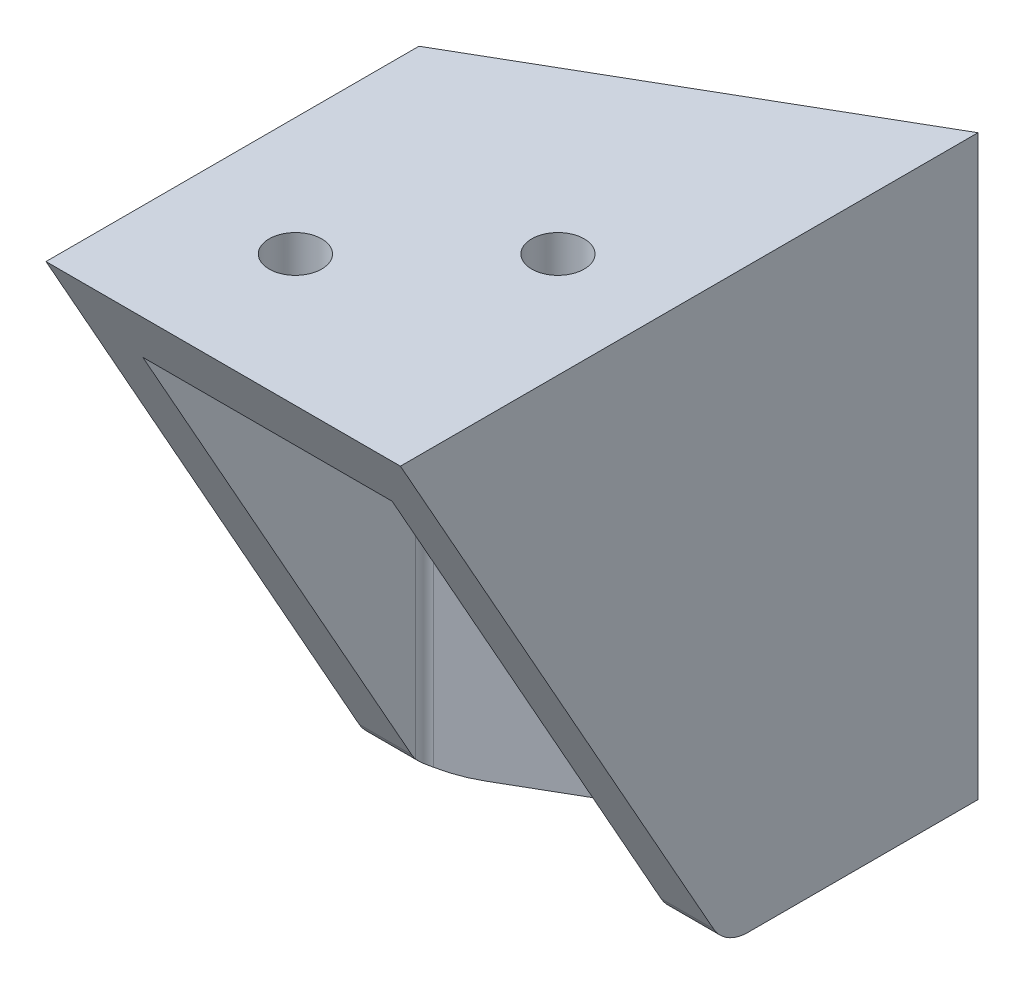
SolidWorks part; units mm, degrees
ref_plane "Front Plane" through (0, 0, 0) normal (0, 0, 1) x (1, 0, 0)
ref_plane "Top Plane" through (0, 0, 0) normal (0, 1, 0) x (1, 0, 0)
ref_plane "Right Plane" through (0, 0, 0) normal (1, 0, 0) x (0, 0, -1)
sketch "Sketch1" plane through (0, 0, 0) normal (0, 1, 0) x (1, 0, 0)
  line L1 (-13.5, -22) -> (13.5, -22)
  line L2 (-13.5, -22) -> (-13.5, 22)
  line L3 (-13.5, 22) -> (13.5, 22)
  line L4 (13.5, -22) -> (13.5, 22)
  line L5 (-13.5, -22) -> (13.5, 22) construction
  line L6 (-13.5, 22) -> (13.5, -22) construction
  point P0 (0, 0)
  dimension "D1" = 27
  dimension "D2" = 44
extrude "Boss-Extrude1" add sketch "Sketch1" along normal blind 6
sketch "Sketch2" plane through (0, 6, 0) normal (0, 1, 0) x (1, 0, 0)
  line L0 (13.5, 22) -> (-13.5, 6.4115)
  line L1 (-13.5, 22) -> (-13.5, -22) construction
  line L2 (-13.5, 6.4115) -> (-13.5, 22)
  line L3 (-13.5, 22) -> (13.5, 22)
  dimension "D1" = 30
extrude "Cut-Extrude1" cut sketch "Sketch2" against normal through all
sketch "Sketch3" plane through (0, 6, 0) normal (0, 1, 0) x (1, 0, 0)
  line L0 (-13.5, 6.4115) -> (13.5, 22)
  line L1 (13.5, 22) -> (13.5, 16)
  line L2 (13.5, -22) -> (13.5, 22) construction
  line L3 (13.5, 16) -> (-13.5, 0.4115)
  line L4 (-13.5, 6.4115) -> (-13.5, -22) construction
  line L5 (-13.5, 0.4115) -> (-13.5, 6.4115)
  dimension "D1" = 6
extrude "Boss-Extrude2" add sketch "Sketch3" against normal blind 44
sketch "Sketch4" plane through (0, 0, 0) normal (0, -1, 0) x (1, 0, 0)
  line L2 (-13.5, 22) -> (13.5, 22) construction
  line L3 (-13.5, -0.4115) -> (-13.5, 22) construction
  circle A0 centre (-4.5, 12) radius 2
  circle A1 centre (5.5, 2) radius 2
  dimension "D5" = 4
  dimension "D6" = 4
  dimension "D1" = 10
  dimension "D2" = 10
  dimension "D3" = 9
  dimension "D4" = 10
extrude "Cut-Extrude2" cut sketch "Sketch4" against normal through all
ref_plane "Plane1" through (-6.1513, 0, -10.6543) normal (-0.5, 0, -0.866) x (-0.866, 0, 0.5)
sketch "Sketch7" plane through (-6.1513, 0, -10.6543) normal (-0.5, 0, -0.866) x (-0.866, 0, 0.5)
  line L2 (-22.6913, -38) -> (8.4856, -38) construction
  line L3 (8.4856, -38) -> (8.4856, 6) construction
  circle A0 centre (-5.5144, -13) radius 2.05
  circle A1 centre (-0.5144, -25.5) radius 2.05
  dimension "D4" = 4.1
  dimension "D5" = 4.1
  dimension "D1" = 12.5
  dimension "D2" = 9
  dimension "D3" = 5
  dimension "D6" = 12.5
extrude "Cut-Extrude4" cut sketch "Sketch7" against normal through all
ref_plane "Plane2" through (-9.5, 0, 0) normal (-1, 0, 0) x (0, 0, 1)
sketch "Sketch12" plane through (-9.5, 0, 0) normal (-1, 0, 0) x (0, 0, 1)
  line L6 (-2.7209, -38) -> (-2.7209, 0)
  line L9 (-2.7209, 0) -> (22, 0)
  line L10 (22, 0) -> (22, -38)
  line L11 (22, -38) -> (-2.7209, -38)
ref_plane "Plane3" through (-13.5, 0, 0) normal (-1, 0, 0) x (0, 0, 1)
ref_plane "Plane4" through (13.5, 0, 0) normal (1, 0, 0) x (0, 0, -1)
ref_plane "Plane5" through (9.5, 0, 0) normal (1, 0, 0) x (0, 0, -1)
sketch "Sketch15" plane through (9.5, 0, 0) normal (1, 0, 0) x (0, 0, -1)
  line L0 (-22, 0) -> (13.6906, 0)
  line L3 (13.6906, 0) -> (13.6906, -38)
  line L7 (-22, 0) -> (-22, -38)
  line L8 (-22, -38) -> (13.6906, -38)
sketch "Sketch17" plane through (13.5, 0, 0) normal (1, 0, 0) x (0, 0, -1)
  line L0 (-22, 0) -> (16, 0)
  line L1 (16, 0) -> (16, -38)
  line L3 (-22, 0) -> (-22, -38)
  line L4 (-22, -38) -> (16, -38)
loft "Loft5" add profiles "Sketch15", "Sketch17"
sketch "Sketch20" plane through (-13.5, 0, 0) normal (-1, 0, 0) x (0, 0, 1)
  line L1 (-0.4115, 0) -> (22, 0)
  line L2 (-0.4115, 0) -> (-0.4115, -38)
  line L3 (-0.4115, -38) -> (22, -38)
  line L4 (22, 0) -> (22, -38)
loft "Loft7" add profiles "Sketch12", "Sketch20"
sketch "Sketch22" plane through (-13.5, 0, 0) normal (-1, 0, 0) x (0, 0, 1)
  line L0 (22, 6) -> (-2.7215, -38)
  line L1 (-6.4115, -38) -> (-0.4115, -38) construction
  line L2 (-6.4115, -38) -> (-6.4115, 6) construction
  line L3 (22, 6) -> (22, -38)
  line L4 (22, -38) -> (-2.7215, -38)
  dimension "D1" = 3.69
extrude "Cut-Extrude6" cut sketch "Sketch22" against normal through all
fillet "Fillet1" radius 1 2 edges
fillet "Fillet2" radius 3 2 edges
